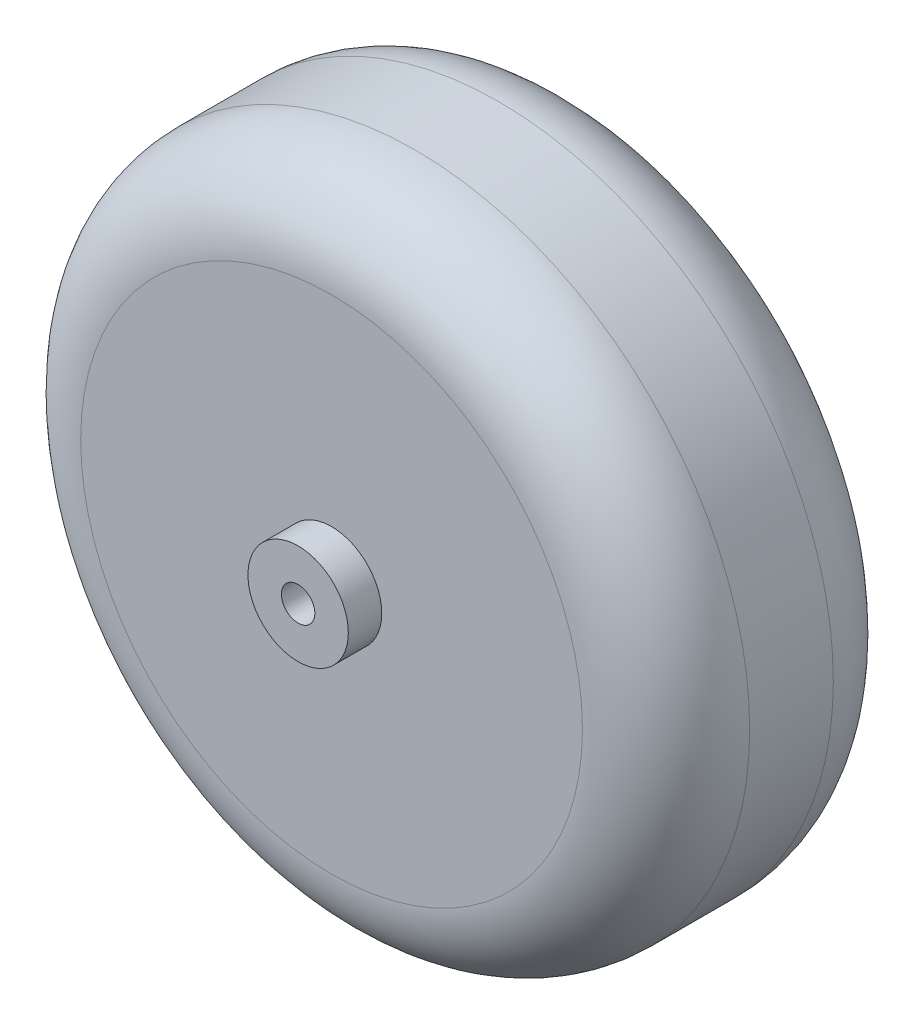
SolidWorks part; units mm, degrees
ref_plane "Front Plane" through (0, 0, 0) normal (0, 0, 1) x (1, 0, 0)
ref_plane "Top Plane" through (0, 0, 0) normal (0, 1, 0) x (1, 0, 0)
ref_plane "Right Plane" through (0, 0, 0) normal (1, 0, 0) x (0, 0, -1)
sketch "Sketch1" plane through (0, 0, 0) normal (0, 0, 1) x (1, 0, 0)
  circle A0 centre (0, 0) radius 20
  dimension "D1" = 40
extrude "Boss-Extrude1" add sketch "Sketch1" along normal mid plane 15 contours A0
fillet "Fillet2" radius 5 2 edges at (20, 0, -7.5) (20, 0, 7.5)
sketch "Sketch2" plane through (0, 0, 7.5) normal (0, 0, 1) x (1, 0, 0)
  circle A0 centre (0, 0) radius 3
  dimension "D1" = 6
extrude "Boss-Extrude2" add sketch "Sketch2" along normal blind 2
sketch "Sketch3" plane through (0, 0, 9.5) normal (0, 0, 1) x (1, 0, 0)
  circle A0 centre (0, 0) radius 1
  dimension "D1" = 2
mirror "Mirror3" about plane through (0, 0, 0) normal (0, 0, 1) of "Boss-Extrude2"
extrude "Cut-Extrude1" cut sketch "Sketch3" against normal through all contours A0
